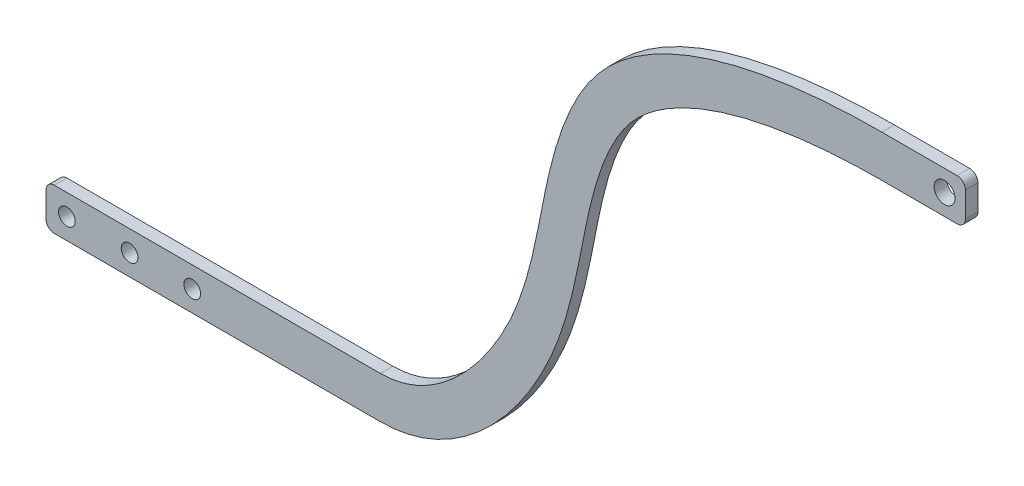
SolidWorks part; units mm, degrees
material "2014 Alloy"
ref_plane "Front Plane" through (0, 0, 0) normal (0, 0, 1) x (1, 0, 0)
ref_plane "Top Plane" through (0, 0, 0) normal (0, 1, 0) x (1, 0, 0)
ref_plane "Right Plane" through (0, 0, 0) normal (1, 0, 0) x (0, 0, -1)
sketch "Sketch1" plane through (0, 0, 0) normal (0, 0, 1) x (1, 0, 0)
  line L0 (0, 0) -> (80, 0)
  line L1 (200, 110) -> (220, 110)
  line L2 (0, -10) -> (80, -10)
  line L3 (200, 100) -> (220, 100)
  line L4 (0, 0) -> (0, -10)
  line L5 (220, 110) -> (220, 100)
  spline S0 degree 3 poles (80, 0) (93.2418, 0) (116.6625, 26.8844) (118.2237, 60.6842) (136.3796, 104.8152) (177.5819, 110) (200, 110) knots 0 0 0 0 0.230202 0.4637 0.593999 1 1 1 1
  spline S1 degree 1 poles (80, -10) (200, 100) knots 0 0 1 1 construction
  spline S2 degree 3 poles (80, -10) (81.3385, -10) (84.0403, -9.814) (89.1719, -8.7734) (95.0961, -6.398) (101.3208, -2.3511) (108.5842, 4.1681) (115.9516, 13.7932) (122.227, 26.3531) (125.8341, 38.4078) (128.0869, 49.6349) (129.761, 58.2391) (131.4392, 64.7119) (133.476, 70.9878) (136.1198, 76.7091) (139.2951, 81.3125) (142.9698, 85.3105) (148.8808, 89.7053) (157.7752, 93.8597) (167.9767, 96.8774) (177.0463, 98.4927) (184.331, 99.3198) (189.7341, 99.7304) (194.1167, 99.9183) (197.5277, 99.989) (199.1707, 100) (200, 100) knots 0 0 0 0 0.015625 0.03125 0.0625 0.09375 0.125 0.1875 0.25 0.3125 0.375 0.4375 0.46875 0.5 0.5625 0.59375 0.625 0.6875 0.75 0.8125 0.875 0.90625 0.9375 0.96875 0.984375 1 1 1 1
  dimension "D2" = 110
  dimension "D3" = 10
  dimension "D4" = 220
  dimension "D1" = 80
  dimension "D5" = 20
extrude "Boss-Extrude1" add sketch "Sketch1" along normal blind 3 contours S0 L1 L5 L3 S2 L2 L4 L0
sketch "Sketch2" plane through (0, 0, 3) normal (0, 0, 1) x (1, 0, 0)
  line L0 (200, 100) -> (220, 100) construction
  line L1 (220, 110) -> (220, 100) construction
  circle A0 centre (215, 105) radius 2.5
  point P6 (220, 105)
  dimension "D2" = 5
  dimension "D3" = 5
  dimension "D1" = 5
extrude "Cut-Extrude1" cut sketch "Sketch2" against normal up to surface (3 mm away) up to face at (110, 36.25, 0)
sketch "Sketch3" plane through (0, 0, 3) normal (0, 0, 1) x (1, 0, 0)
  line L0 (0, 0) -> (0, -10) construction
  line L1 (0, -10) -> (80, -10) construction
  circle A0 centre (5, -5) radius 2
  circle A1 centre (20, -5) radius 2
  circle A2 centre (35, -5) radius 2
  dimension "D1" = 4
  dimension "D2" = 5
  dimension "D3" = 5
  dimension "D4" = 3
extrude "Cut-Extrude2" cut sketch "Sketch3" against normal up to surface (3 mm away) up to face at (212.5, 105, 0)
fillet "Fillet1" radius 2 4 edges at (0, -10, 1.5) (0, 0, 1.5) (220, 100, 1.5) (220, 110, 1.5)
equation "\"barWidth\"=10"
equation "\"D3@Sketch3\"=\"barWidth\"/2"
equation "\"D1@Sketch2\"=\"barWidth\"/2"
